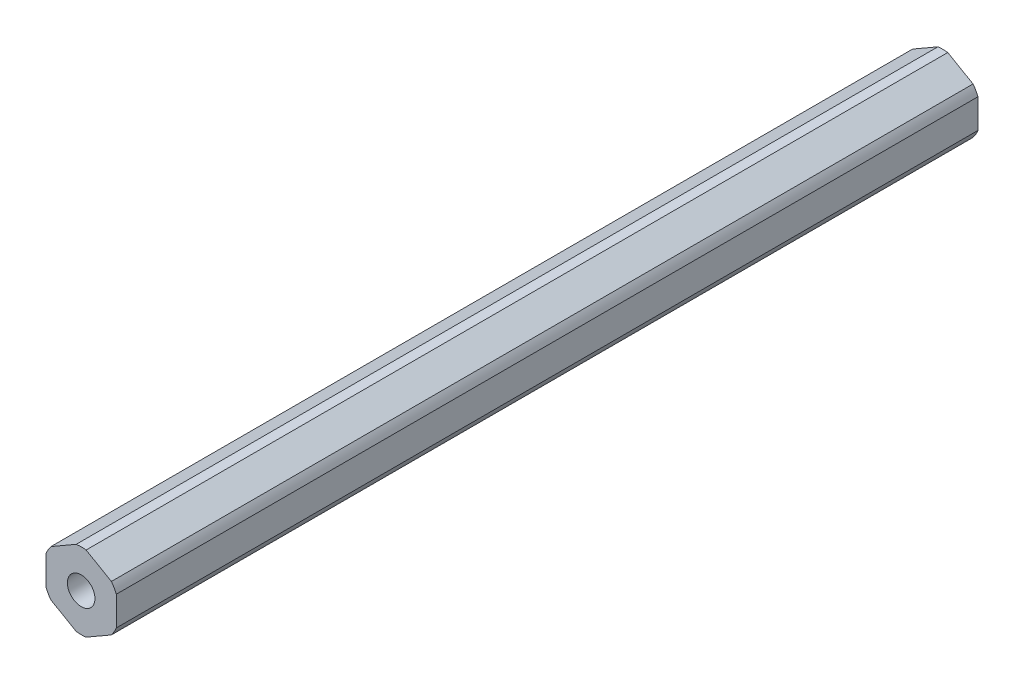
SolidWorks part; units mm, degrees
material "7075-T6 (SN)"
ref_plane "Front Plane" through (0, 0, 0) normal (0, 0, 1) x (1, 0, 0)
ref_plane "Top Plane" through (0, 0, 0) normal (0, 1, 0) x (1, 0, 0)
ref_plane "Right Plane" through (0, 0, 0) normal (1, 0, 0) x (0, 0, -1)
sketch "Sketch2" plane through (0, 0, 0) normal (0, 0, 1) x (1, 0, 0)
  line L1 (-0.893, 6.8168) -> (-5.457, 4.1818)
  line L2 (-6.35, 2.635) -> (-6.35, -2.635)
  line L3 (-5.457, -4.1818) -> (-0.893, -6.8168)
  line L4 (0.893, -6.8168) -> (5.457, -4.1818)
  line L5 (6.35, -2.635) -> (6.35, 2.635)
  line L6 (5.457, 4.1818) -> (0.893, 6.8168)
  arc A0 (-5.457, 4.1818) -> (-6.35, 2.635) centre (0, 0) ccw
  circle A1 centre (0, 0) radius 6.35 construction
  arc A2 (-6.35, -2.635) -> (-5.457, -4.1818) centre (0, 0) ccw
  arc A3 (-0.893, -6.8168) -> (0.893, -6.8168) centre (0, 0) ccw
  arc A4 (5.457, -4.1818) -> (6.35, -2.635) centre (0, 0) ccw
  arc A5 (6.35, 2.635) -> (5.457, 4.1818) centre (0, 0) ccw
  arc A6 (0.893, 6.8168) -> (-0.893, 6.8168) centre (0, 0) ccw
  circle A7 centre (0, 0) radius 2.4892
  dimension "D1" = 12.7
  dimension "D2" = 13.75
  dimension "D3" = 4.9784
extrude "Boss-Extrude1" add sketch "Sketch2" against normal blind 155.575
